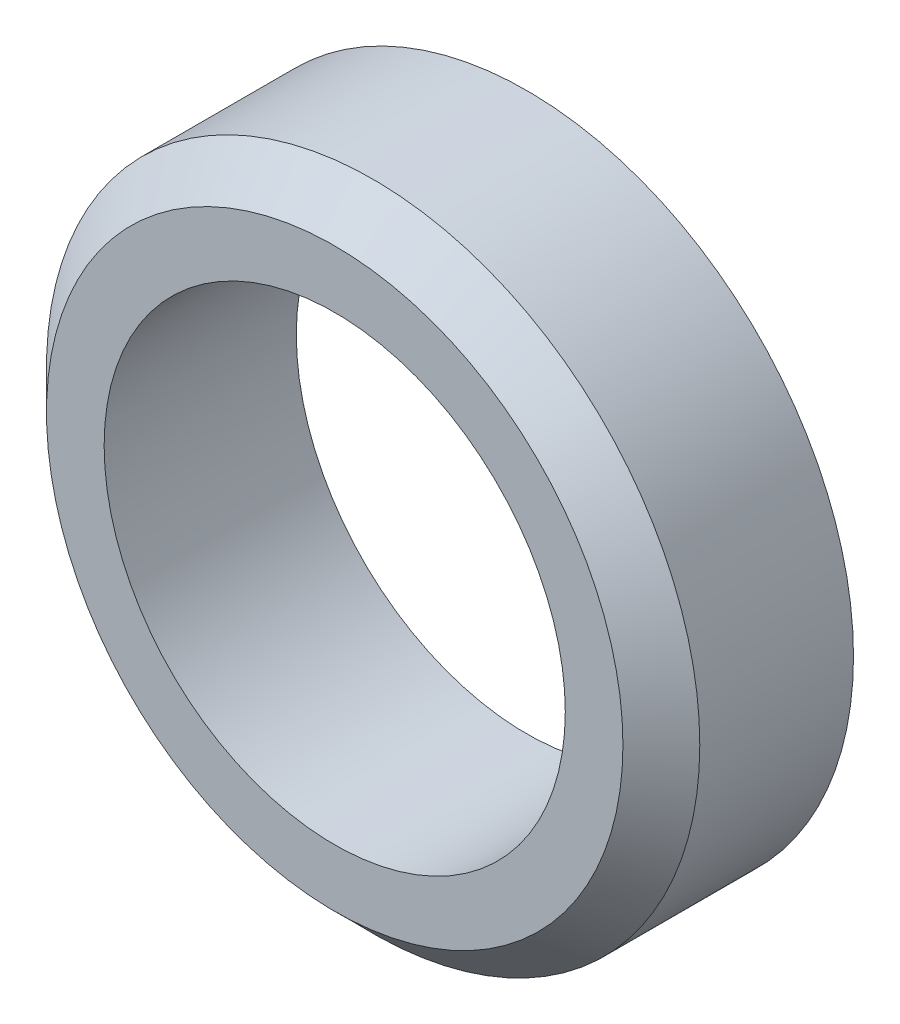
SolidWorks part; units mm, degrees
ref_plane "Спереди" through (0, 0, 0) normal (0, 0, 1) x (1, 0, 0)
ref_plane "Сверху" through (0, 0, 0) normal (0, 1, 0) x (1, 0, 0)
ref_plane "Справа" through (0, 0, 0) normal (1, 0, 0) x (0, 0, -1)
sketch "Эскиз1" plane through (0, 0, 0) normal (0, 0, 1) x (1, 0, 0)
  circle A0 centre (0, 0) radius 42.5
  point P3 (-138.9687, 38.0454)
extrude "Бобышка-Вытянуть1" add sketch "Эскиз1" along normal blind 25
chamfer "Фаска1" distance 5 angle 45 1 edges at (42.5, 0, 25)
sketch "Эскиз2" plane through (0, 0, 0) normal (0, 0, -1) x (-1, 0, 0)
  circle A0 centre (0, 0) radius 30
extrude "Вырез-Вытянуть1" cut sketch "Эскиз2" against normal through all
